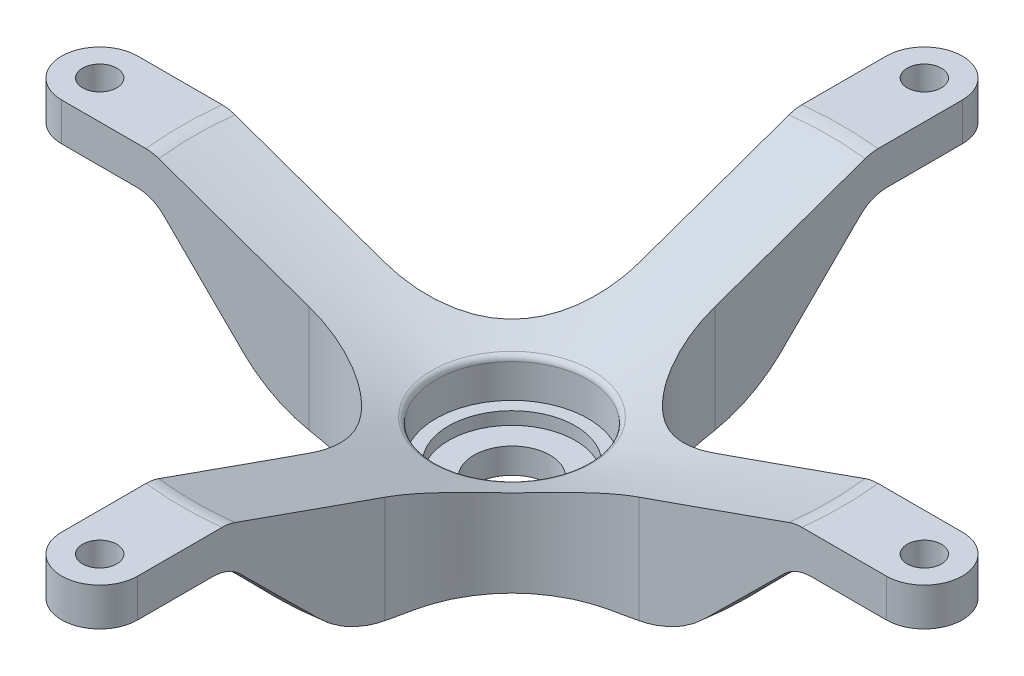
SolidWorks part; units mm, degrees
ref_plane "Plan de face" through (0, 0, 0) normal (0, 0, 1) x (1, 0, 0)
ref_plane "Plan de dessus" through (0, 0, 0) normal (0, 1, 0) x (1, 0, 0)
ref_plane "Plan de droite" through (0, 0, 0) normal (1, 0, 0) x (0, 0, -1)
sketch "Esquisse1" plane through (0, 0, 0) normal (0, 0, 1) x (1, 0, 0)
  line L0 (0, 5.0776) -> (0, -4.1872) construction
  line L1 (-11.3829, 0) -> (-3, 0)
  line L4 (-26.7676, 10) -> (-35.525, 10)
  line L5 (-35.525, 10) -> (-35.525, 13)
  line L10 (-26.0465, 13) -> (-35.525, 13)
  line L13 (-6, 5.6481) -> (-6, 3)
  line L14 (-6, 3) -> (-5, 3)
  line L15 (-5, 3) -> (-5, 2)
  line L16 (-5, 2) -> (-3, 2)
  line L17 (-3, 2) -> (-3, 0)
  line L18 (-24.6463, 9.1213) -> (-18.4539, 2.9289)
  line L19 (-25.0341, 12.824) -> (-6.3313, 6.1188)
  arc A11 (-11.3829, 0) -> (-18.4539, 2.9289) centre (-11.3829, 10) cw
  arc A12 (-25.0341, 12.824) -> (-26.0465, 13) centre (-26.0465, 10) ccw
  arc A13 (-26.7676, 10) -> (-24.6463, 9.1213) centre (-26.7676, 7) cw
  arc A14 (-6.3313, 6.1188) -> (-6, 5.6481) centre (-6.5, 5.6481) cw
  point P1 (0, 0)
  point P5 (-24.5312, 22.8639)
  point P6 (-6.684, 0.106)
  point P12 (-23.209, 6.1206)
  point P13 (-32.525, 13)
  point P16 (-21.1108, 6.4142)
  point P17 (-16.1108, 1.4142)
  point P18 (-4, 1.9854)
  point P19 (-4, 3)
  point P20 (0, 0)
  point P25 (-25.525, 13)
  point P29 (-25.525, 10)
  point P34 (-6, 6)
  point P38 (-25.525, 10)
  dimension "D12" = 10
  dimension "D13" = 1
  dimension "D15" = 3
  dimension "D16" = 0.5
  dimension "D2" = 12
  dimension "D3" = 3
  dimension "D4" = 65.05
  dimension "D5" = 10
  dimension "D6" = 3
  dimension "D7" = 45
  dimension "D8" = 1
  dimension "D9" = 3
  dimension "D10" = 10
  dimension "D11" = 6
  dimension "D14" = 2
revolve "Révolution1" add sketch "Esquisse1" angle 360 about L0
hole_wizard "Dégagement M2.51" positions "Esquisse2" profile "Esquisse3" hole size "M2.5" standard "ISO" end condition through all
sketch "Esquisse2" plane through (0, 13, 0) normal (0, 1, 0) x (1, 0, 0)
  point P0 (-32.525, 0)
sketch "Esquisse3" plane through (-32.525, 13, 0) normal (1, 0, 0) x (0, 0, 1)
  line L0 (0, 0) -> (0, 13)
  line L1 (0, 13) -> (1.35, 13)
  line L2 (1.35, 13) -> (1.35, 0)
  line L5 (1.35, 0) -> (0, 0)
  line L11 (0, -6.35) -> (0, 107.95) construction
  dimension "Diamètre du perçage jusqu'au prochain" = 2.7
  dimension "Profondeur du perçage jusqu'au prochain" = 13
pattern_circular "Répétition circulaire1" count 4 over 360 about axis through (0, 0, 0) along (0, 1, 0) of "Dégagement M2.51"
sketch "Esquisse4" plane through (0, 13, 0) normal (0, 1, 0) x (1, 0, 0)
  line L0 (0, 32.525) -> (0, -32.525) construction
  line L1 (3, 32.525) -> (3, 13)
  line L2 (-3, 32.525) -> (-3, 13)
  line L3 (-32.525, 0) -> (32.525, 0) construction
  line L4 (-32.525, 3) -> (-13, 3)
  line L5 (-32.525, -3) -> (-13, -3)
  line L6 (13, 3) -> (32.525, 3)
  line L7 (3, -13) -> (3, -32.525)
  line L8 (13, -3) -> (32.525, -3)
  line L9 (-3, -13) -> (-3, -32.525)
  arc A0 (3, 32.525) -> (-3, 32.525) centre (0, 32.525) ccw
  arc A1 (-3, -32.525) -> (3, -32.525) centre (0, -32.525) ccw
  arc A2 (-32.525, 3) -> (-32.525, -3) centre (-32.525, 0) ccw
  arc A3 (32.525, -3) -> (32.525, 3) centre (32.525, 0) ccw
  circle A4 centre (0, 0) radius 35.525 construction
  circle A5 centre (0, 0) radius 35.525
  arc A6 (-13, -3) -> (-3, -13) centre (-13, -13) cw
  arc A7 (3, -13) -> (13, -3) centre (13, -13) cw
  arc A8 (3, 13) -> (13, 3) centre (13, 13) ccw
  arc A9 (-13, 3) -> (-3, 13) centre (-13, 13) ccw
  point P4 (0, 0)
  point P9 (0, 0)
  point P20 (0, 0)
  point P28 (-3, -3)
  point P31 (3, -3)
  point P36 (0, 0)
  point P37 (0, 0)
  dimension "D1" = 10
extrude "Enlèv. mat.-Extru.1" cut sketch "Esquisse4" against normal through all
